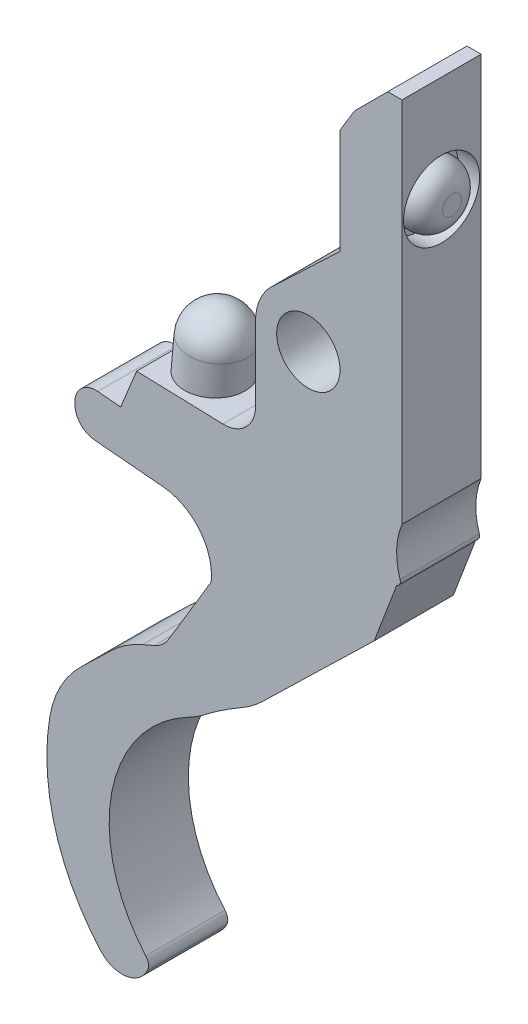
SolidWorks part; units mm, degrees
ref_plane "정면" through (0, 0, 0) normal (0, 0, 1) x (1, 0, 0)
ref_plane "윗면" through (0, 0, 0) normal (0, 1, 0) x (1, 0, 0)
ref_plane "우측면" through (0, 0, 0) normal (1, 0, 0) x (0, 0, -1)
sketch "스케치1" plane through (0, 0, 0) normal (0, 0, 1) x (1, 0, 0)
  line L0 (7.5189, 25.0781) -> (8.8664, 25.0781)
  line L1 (7.5189, 25.0781) -> (4.3842, 21.9434)
  line L2 (8.8664, 25.0781) -> (8.8664, -9.7282)
  line L3 (-5, 0) -> (-5, -10.0714)
  line L4 (-17.7666, -13.4266) -> (-19.9405, -13.2288)
  line L5 (2.9878, 19.65) -> (2.9878, 17.6612)
  line L6 (-20.2877, -17.3633) -> (-13.717, -17.9611)
  line L7 (2.9878, 17.6612) -> (2.9878, 9.7088)
  line L8 (2.9878, 9.7088) -> (-3.1847, 3.8546)
  line L9 (8.3701, -14.9782) -> (6.2381, -20.6005)
  line L10 (2.2148, 21.9434) -> (17.8049, 21.9434) construction
  line L11 (4.3842, 21.9434) -> (2.9878, 19.65)
  line L12 (6.2381, -20.6005) -> (-4.3386, -30.8592)
  line L13 (-5, -10.0714) -> (-16.2648, -9.7282)
  line L14 (-16.2648, -9.7282) -> (-17.7666, -13.4266)
  line L16 (-9.201, -23.497) -> (-13.2181, -30.1935)
  line L17 (-18.7012, -33.8794) -> (-21.5874, -36.6789)
  line L18 (-15.6804, -31.8671) -> (-14.6082, -31.4073)
  circle A0 centre (0, 0) radius 3
  circle A1 centre (0, 0) radius 5
  arc A2 (-6.3376, -32.3623) -> (-4.3386, -30.8592) centre (-11.3009, -23.681) ccw
  arc A3 (-6.3376, -32.3623) -> (-9.8499, -34.7011) centre (9.0543, -59.2837) ccw
  arc A4 (-24.4913, -42.2266) -> (-19.6524, -58.9718) centre (-4.5193, -45.5271) ccw
  arc A5 (-22.1027, -15.4958) -> (-20.2877, -17.3633) centre (-20.1065, -15.3716) ccw
  arc A6 (-19.9405, -13.2288) -> (-22.1027, -15.4958) centre (-20.1217, -15.2206) ccw
  arc A7 (8.8664, -9.7282) -> (8.6919, -14.3466) centre (15.0215, -12.2733) ccw
  arc A8 (8.6919, -14.3466) -> (8.3701, -14.9782) centre (8.2168, -14.5023) cw
  arc A9 (-13.717, -17.9611) -> (-9.201, -23.497) centre (-14.17, -22.9405) cw
  arc A10 (-11.3342, -35.6471) -> (-9.8499, -34.7011) centre (-15.9459, -26.774) ccw
  arc A11 (-21.5874, -36.6789) -> (-24.4913, -42.2266) centre (-14.6251, -43.857) ccw
  arc A12 (-19.6524, -58.9718) -> (-15.2319, -58.3761) centre (-17.6426, -57.1863) ccw
  arc A13 (-15.3951, -57.2539) -> (-11.3342, -35.6471) centre (-4.8916, -48.043) cw
  arc A14 (-15.2319, -58.3761) -> (-15.3951, -57.2539) centre (-16.1286, -57.9335) ccw
  arc A15 (-18.7012, -33.8794) -> (-15.6804, -31.8671) centre (-11.7388, -41.0576) cw
  arc A16 (-14.6082, -31.4073) -> (-13.2181, -30.1935) centre (-15.7907, -28.6502) ccw
  dimension "D1" = 6
  dimension "D2" = 10
  dimension "D4" = 2
  dimension "D5" = 0.5
  dimension "D6" = 5
  dimension "D7" = 10
  dimension "D8" = 3
  dimension "D9" = 1
  dimension "D3" = 45
extrude "보스-돌출1" add sketch "스케치1" along normal blind 7.5
sketch "스케치2" plane through (8.8664, 0, 0) normal (1, 0, 0) x (0, 0, -1)
  line L0 (-7.5, 25.0781) -> (0, 25.0781) construction
  line L1 (0, 25.0781) -> (0, -9.7282) construction
  circle A0 centre (-3.75, 15.0781) radius 3.6
  dimension "D1" = 7.2
  dimension "D2" = 10
  dimension "D3" = 3.75
extrude "컷-돌출1" cut sketch "스케치2" against normal blind 2
sketch "스케치3" plane through (6.8664, 0, 0) normal (1, 0, 0) x (0, 0, -1)
  circle A0 centre (-3.75, 15.0781) radius 2.9
  dimension "D1" = 5.8
extrude "보스-돌출2" add sketch "스케치3" along normal blind 3
fillet "필렛1" radius 2 1 edges at (9.8664, 17.9781, 3.75)
sketch "스케치4" plane through (-1.3573, -14.9194, 0) normal (0.0906, 0.9959, 0) x (0.9959, -0.0906, 0)
  line L0 (-3.6578, -7.5) -> (-3.6578, 0) construction
  line L1 (-4.067, 0) -> (-15.3165, 0) construction
  circle A0 centre (-11.6576, -3.8) radius 2.9
  point P2 (-3.6578, -3.75)
  dimension "D1" = 5.8
  dimension "D2" = 8
  dimension "D3" = 3.8
extrude "보스-돌출3" add sketch "스케치4" along normal blind 10
fillet "필렛2" radius 2.9 1 edges at (-14.949, -3.6416, 3.8)
fillet "필렛3" radius 3 1 edges at (-5, -10.0714, 3.75)
